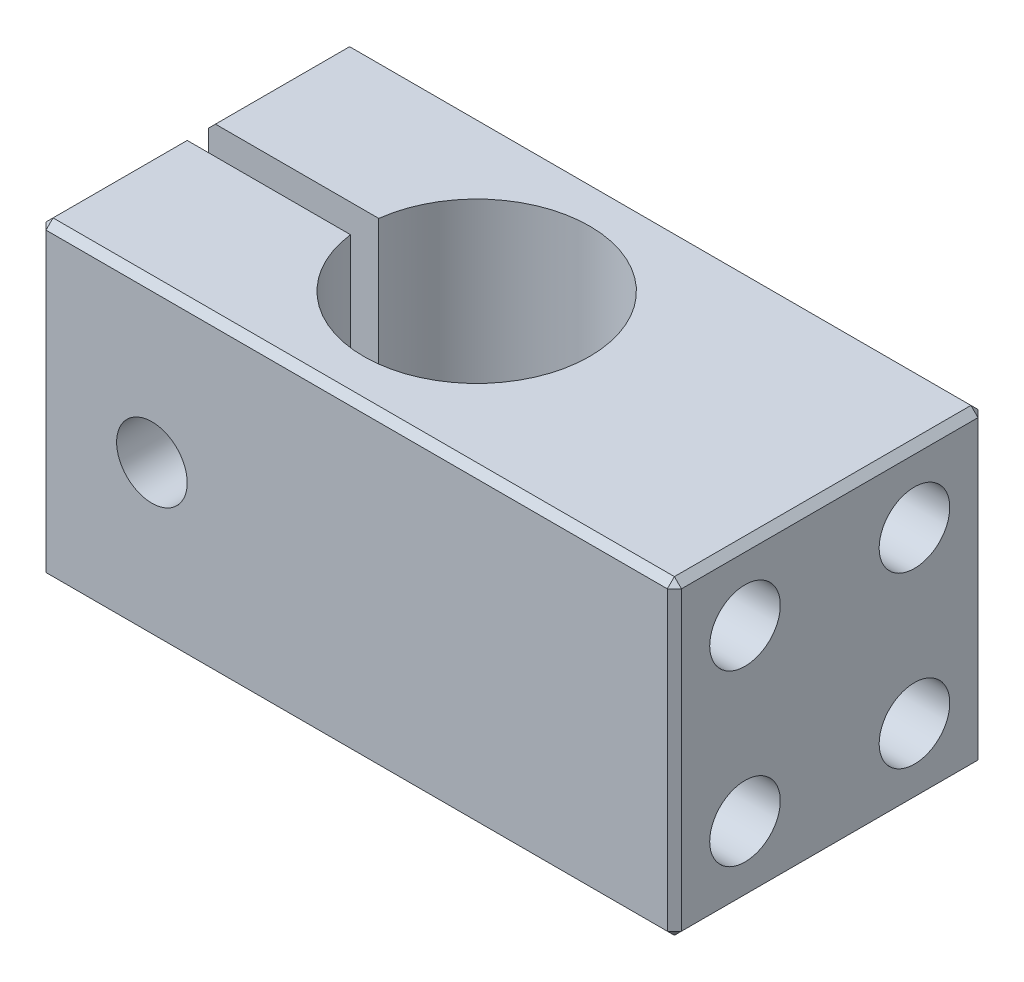
SolidWorks part; units mm, degrees
ref_plane "前视基准面" through (0, 0, 0) normal (0, 0, 1) x (1, 0, 0)
ref_plane "上视基准面" through (0, 0, 0) normal (0, 1, 0) x (1, 0, 0)
ref_plane "右视基准面" through (0, 0, 0) normal (1, 0, 0) x (0, 0, -1)
other "Configuration Table"
sketch "草图5" plane through (0, 0, 0) normal (0, 1, 0) x (1, 0, 0)
  line L1 (-22.5, -11) -> (22.5, -11)
  line L2 (-22.5, -11) -> (-22.5, 11)
  line L3 (-22.5, 11) -> (22.5, 11)
  line L4 (22.5, -11) -> (22.5, 11)
  line L5 (-22.5, -11) -> (22.5, 11) construction
  line L6 (-22.5, 11) -> (22.5, -11) construction
  point P0 (0, 0)
  dimension "D1" = 45
  dimension "D2" = 22
extrude "凸台-拉伸2" add sketch "草图5" along normal blind 22
sketch "草图6" plane through (0, 0, 0) normal (0, 1, 0) x (1, 0, 0)
  line L0 (-2.5, 11) -> (-2.5, -11) construction
  line L1 (22.5, 11) -> (-22.5, 11) construction
  line L2 (-22.5, -11) -> (22.5, -11) construction
  line L3 (-22.5, 11) -> (-22.5, -11) construction
  line L4 (-22.5, 0) -> (22.5, 0) construction
  line L5 (22.5, -11) -> (22.5, 11) construction
  line L6 (-22.5, -1) -> (-22.5, 1)
  line L7 (-22.5, 1) -> (-10.4373, 1)
  line L8 (-22.5, -1) -> (-10.4373, -1)
  arc A0 (-10.4373, -1) -> (-10.4373, 1) centre (-2.5, 0) ccw
  point P16 (-22.5, 0)
  dimension "D2" = 16
  dimension "D1" = 20
  dimension "D3" = 2
extrude "切除-拉伸3" cut sketch "草图6" along normal up to surface (22 mm away) from surface at 0 up to face at (0, 22, 0) starting at face at (0, 0, 0)
sketch "草图7" plane through (0, 0, 0) normal (1, 0, 0) x (0, 0, -1)
  line L0 (-11, 22) -> (11, 0) construction
  line L1 (11, 22) -> (-11, 0) construction
  line L3 (-6, 5) -> (6, 5) construction
  line L4 (-6, 5) -> (-6, 17) construction
  line L5 (-6, 17) -> (6, 17) construction
  line L6 (6, 5) -> (6, 17) construction
  line L7 (-6, 5) -> (6, 17) construction
  line L8 (-6, 17) -> (6, 5) construction
  circle A0 centre (-6, 17) radius 2.5
  circle A1 centre (-6, 5) radius 2.5
  circle A2 centre (6, 17) radius 2.5
  circle A3 centre (6, 5) radius 2.5
  point P8 (0, 11)
  dimension "D2" = 5
  dimension "D3" = 5
  dimension "D4" = 5
  dimension "D5" = 5
  dimension "D1" = 12
extrude "切除-拉伸4" cut sketch "草图7" against normal blind 10 from surface at 22.5 starting at face at (22.5, 11, 0)
sketch "草图8" plane through (0, 0, 0) normal (0, 0, 1) x (1, 0, 0)
  line L0 (-2.5, 22) -> (-2.5, 0) construction
  line L1 (-22.5, 22) -> (22.5, 22) construction
  line L2 (-22.5, 0) -> (22.5, 0) construction
  line L3 (-22.5, 22) -> (-22.5, 0) construction
  line L4 (-22.5, 11) -> (22.5, 11) construction
  line L5 (22.5, 22) -> (22.5, 0) construction
  line L6 (-14.5, 22) -> (-14.5, 0) construction
  circle A0 centre (-14.5, 11) radius 2.5
  dimension "D3" = 5
  dimension "D1" = 20
  dimension "D2" = 12
extrude "切除-拉伸5" cut sketch "草图8" against normal up to surface (22 mm away) from surface at 11 up to face at (0, 11, -11) starting at face at (0, 11, 11)
chamfer "倒角1" distance 0.5 angle 45 14 edges at (-22.5, 11, 11) (-22.5, 22, 6) (-22.5, 22, -6) (-22.5, 11, -11) (-22.5, 0, -6) (-22.5, 0, 6) (0, 0, -11) (22.5, 0, 0) (0, 0, 11) (22.5, 11, 11) (22.5, 11, -11) (0, 22, -11) (22.5, 22, 0) (0, 22, 11)
